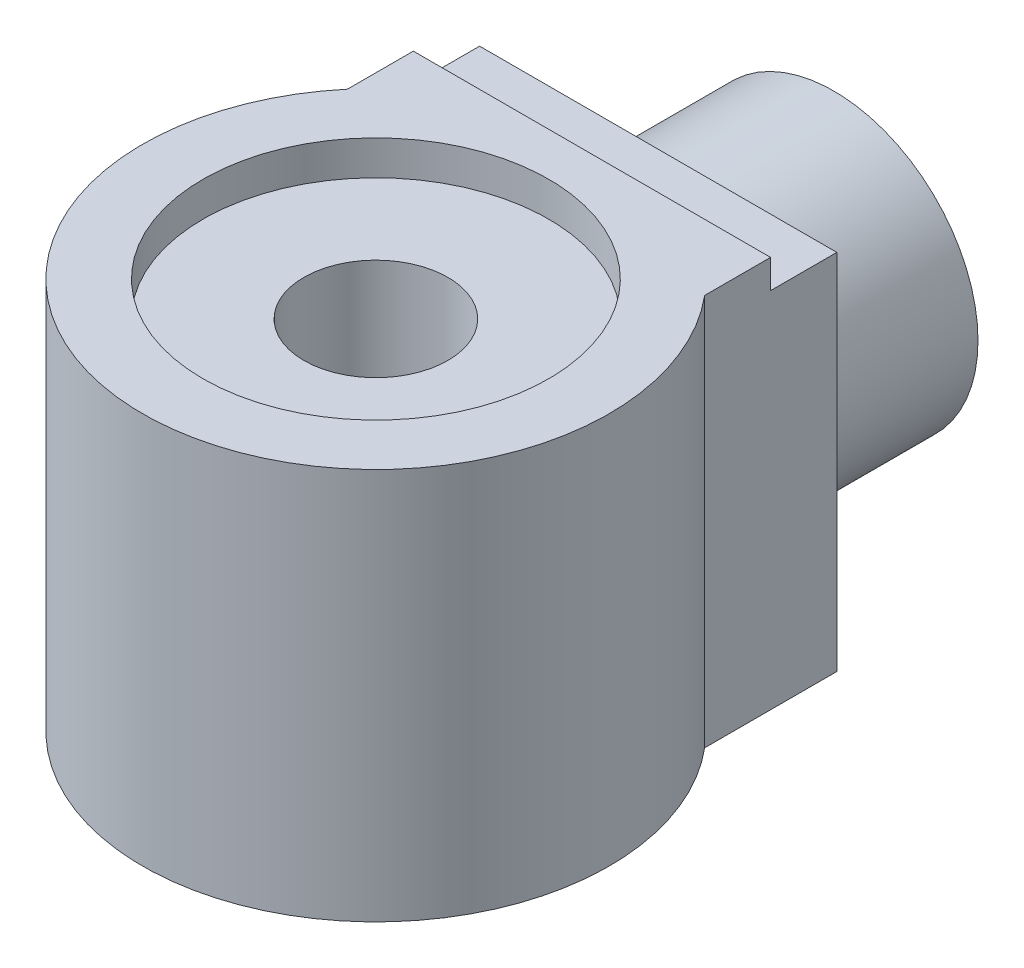
SolidWorks part; units mm, degrees
ref_plane "Front Plane" through (0, 0, 0) normal (0, 0, 1) x (1, 0, 0)
ref_plane "Top Plane" through (0, 0, 0) normal (0, 1, 0) x (1, 0, 0)
ref_plane "Right Plane" through (0, 0, 0) normal (1, 0, 0) x (0, 0, -1)
sketch "Sketch1" plane through (0, 0, 0) normal (0, 1, 0) x (1, 0, 0)
  line L0 (0, 0) -> (0, 10.5961) construction
  line L2 (15.748, 24.892) -> (-15.748, 24.892)
  line L3 (15.748, 24.892) -> (15.748, 13.2397)
  line L5 (-15.748, 24.892) -> (-15.748, 13.2397)
  line L6 (15.748, 24.892) -> (-15.748, -20.574) construction
  line L7 (15.748, -20.574) -> (-15.748, 24.892) construction
  arc A0 (-15.748, 13.2397) -> (15.748, 13.2397) centre (0, 0) ccw
  point P3 (0, 2.159)
  dimension "D1" = 41.148
  dimension "D2" = 45.466
  dimension "D3" = 31.496
  dimension "D4" = 2.159
extrude "Boss-Extrude1" add sketch "Sketch1" along normal blind 34.544
sketch "Sketch2" plane through (0, 34.544, 0) normal (0, 1, 0) x (1, 0, 0)
  circle A0 centre (0, 0) radius 15.24
  dimension "D1" = 30.48
extrude "Cut-Extrude1" cut sketch "Sketch2" against normal blind 3.048
hole_wizard "1/2 (0.5) Diameter Hole1" positions "Sketch3" profile "Sketch4" hole size "1/2" standard "ANSI Inch" end condition through all
sketch "Sketch3" plane through (0, 31.496, 0) normal (0, 1, 0) x (1, 0, 0)
  point P0 (0, 0)
sketch "Sketch4" plane through (0, 31.496, 0) normal (1, 0, 0) x (0, 0, 1)
  line L0 (0, 0) -> (0, 31.496)
  line L1 (0, 31.496) -> (6.35, 31.496)
  line L2 (6.35, 31.496) -> (6.35, 0)
  line L5 (6.35, 0) -> (0, 0)
  line L11 (0, -6.35) -> (0, 107.95) construction
  dimension "Thru Hole Dia." = 12.7
  dimension "Thru Hole Depth" = 31.496
sketch "Sketch5" plane through (0, 34.544, 0) normal (0, 1, 0) x (1, 0, 0)
  line L0 (15.748, 13.2397) -> (15.748, 24.892) construction
  line L1 (-15.748, 24.892) -> (15.748, 24.892)
  line L2 (-15.748, 24.892) -> (-15.748, 19.05)
  line L3 (-15.748, 19.05) -> (15.748, 19.05)
  line L4 (15.748, 24.892) -> (15.748, 19.05)
  dimension "D1" = 5.842
extrude "Cut-Extrude2" cut sketch "Sketch5" against normal blind 2.54
sketch "Sketch8" plane through (0, 0, -24.892) normal (0, 0, -1) x (-1, 0, 0)
  line L0 (-15.748, 32.004) -> (15.748, 0) construction
  circle A0 centre (0, 16.002) radius 10.668
  circle A1 centre (0, 16.002) radius 12.7
  dimension "D1" = 25.4
  dimension "D2" = 2.032
extrude "Boss-Extrude3" add sketch "Sketch8" along normal blind 15.494
sketch "Sketch9" plane through (0, 0, -24.892) normal (0, 0, -1) x (-1, 0, 0)
  circle A0 centre (0, 16.002) radius 6.477
  dimension "D1" = 12.954
extrude "Boss-Extrude4" add sketch "Sketch9" along normal blind 19.05
sketch "Sketch6" plane through (0, 0, -24.892) normal (0, 0, -1) x (-1, 0, 0)
  line L0 (-15.748, 32.004) -> (15.748, 0) construction
  circle A0 centre (0, 16.002) radius 12.7
  dimension "D1" = 25.4
extrude "Boss-Extrude2" add sketch "Sketch6" along normal blind 15.494
sketch "Sketch7" plane through (0, 0, -40.386) normal (0, 0, -1) x (-1, 0, 0)
  circle A0 centre (0, 16.002) radius 6.477
  circle A1 centre (0, 16.002) radius 10.668
  circle A3 centre (0, 16.002) radius 12.7 construction
  circle A4 centre (0, 16.002) radius 12.7 construction
  dimension "D1" = 12.954
  dimension "D2" = 2.032
  dimension "D3" = 21.336
extrude "Cut-Extrude3" cut sketch "Sketch7" against normal blind 15.494
